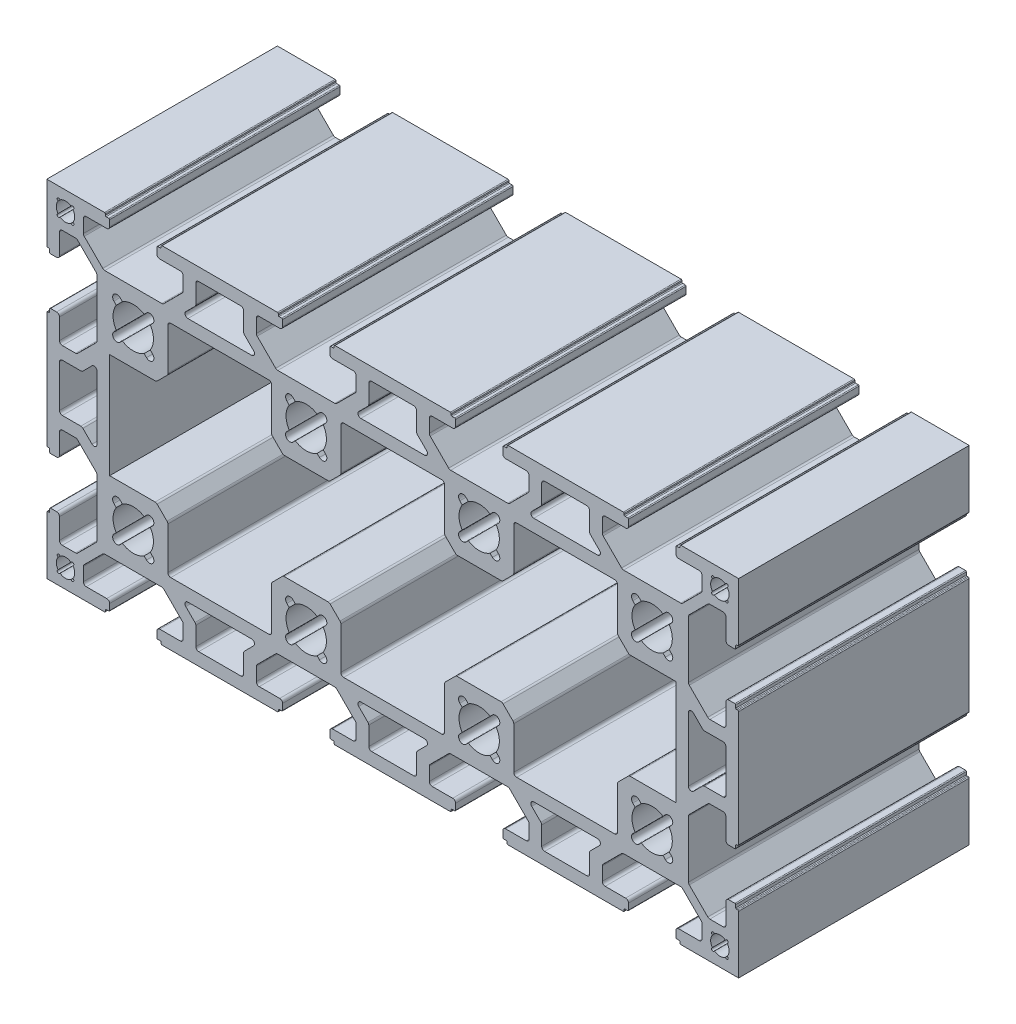
SolidWorks part; units mm, degrees
material "6061 Alaşım"
ref_plane "Ön Düzlem" through (0, 0, 0) normal (0, 0, 1) x (1, 0, 0)
ref_plane "Üst Düzlem" through (0, 0, 0) normal (0, 1, 0) x (1, 0, 0)
ref_plane "Sağ Düzlem" through (0, 0, 0) normal (1, 0, 0) x (0, 0, -1)
sketch "Referans" plane through (0, 0, 0) normal (0, 0, 1) x (1, 0, 0)
  line L0 (-15, 30) -> (-15, 0) construction
  line L1 (-60, -30) -> (60, -30) construction
  line L2 (-60, -30) -> (-60, 30) construction
  line L3 (-60, 30) -> (60, 30) construction
  line L4 (60, -30) -> (60, 30) construction
  line L5 (0, 30) -> (0, -30) construction
  line L6 (-60, 0) -> (60, 0) construction
  line L7 (-45, 30) -> (-45, 0) construction
  line L8 (-56.75, 30) -> (-56.75, 0) construction
  line L9 (-60, 26.75) -> (-56.75, 26.75) construction
  line L10 (-30, 30) -> (-30, 0) construction
  point P0 (0, 0)
  dimension "D1" = 120
  dimension "D2" = 60
  dimension "D3" = 30
  dimension "D4" = 15
  dimension "D5" = 56.75
  dimension "D6" = 26.75
  dimension "D7" = 15
sketch "Çizim3" plane through (0, 0, 0) normal (0, 0, 1) x (1, 0, 0)
  line L0 (-10.9, 28.3) -> (-10.9, 29.35)
  line L1 (-10.75, 29.5) -> (-10.3, 29.5)
  line L2 (-10.15, 29.65) -> (-10.15, 29.85)
  line L3 (-60, 30) -> (60, 30) construction
  line L4 (-10, 30) -> (10, 30)
  line L5 (-10.4, 27.8) -> (-6.85, 27.8)
  line L6 (-6.35, 27.3) -> (-6.35, 25.0071)
  line L7 (-6.4964, 24.6536) -> (-9.7036, 21.4464)
  line L8 (-10.0571, 21.3) -> (-19.9429, 21.3)
  line L9 (-15, 30) -> (-15, 0) construction
  line L10 (5.5316, 21.3) -> (-5.5316, 21.3)
  line L11 (-5.8852, 22.1536) -> (-4.2964, 23.7423)
  line L12 (-4.15, 24.0958) -> (-4.15, 27.3)
  line L13 (-3.65, 27.8) -> (3.65, 27.8)
  line L14 (0, 30) -> (0, -30) construction
  line L15 (-60, 0) -> (60, 0) construction
  line L16 (8.5, 19.1) -> (-8.5, 19.1)
  line L17 (-9, 18.6) -> (-9, 9.1) construction
  line L18 (-9, 9.1) -> (-21, 9.1) construction
  line L19 (0, 30) -> (0, 27.8) construction
  line L20 (0, 21.3) -> (0, 19.1) construction
  line L21 (-15, 21.3) -> (-15, 9.1) construction
  line L22 (-23.5036, 24.6536) -> (-20.2964, 21.4464)
  line L23 (-23.65, 27.3) -> (-23.65, 25.0071)
  line L24 (-19.6, 27.8) -> (-23.15, 27.8)
  line L25 (-19.1, 28.3) -> (-19.1, 29.35)
  line L26 (-19.25, 29.5) -> (-19.7, 29.5)
  line L27 (-19.85, 29.65) -> (-19.85, 29.85)
  line L28 (-20, 30) -> (-40, 30)
  line L29 (-30, 30) -> (-30, 27.8) construction
  line L30 (-26.35, 27.8) -> (-33.65, 27.8)
  line L31 (-25.85, 24.0958) -> (-25.85, 27.3)
  line L32 (-24.1148, 22.1536) -> (-25.7036, 23.7423)
  line L33 (-35.5316, 21.3) -> (-24.4684, 21.3)
  line L34 (-30, 21.3) -> (-30, 19.1) construction
  line L35 (-38.5, 19.1) -> (-21.5, 19.1)
  line L36 (-21, 18.6) -> (-21, 9.1) construction
  line L39 (-39, 18.6) -> (-39, 11.3071)
  line L40 (-35.8852, 22.1536) -> (-34.2964, 23.7423)
  line L41 (-34.15, 24.0958) -> (-34.15, 27.3)
  line L42 (-40.15, 29.65) -> (-40.15, 29.85)
  line L43 (-40.75, 29.5) -> (-40.3, 29.5)
  line L44 (-40.9, 28.3) -> (-40.9, 29.35)
  line L45 (-40.4, 27.8) -> (-36.85, 27.8)
  line L46 (-36.35, 27.3) -> (-36.35, 25.0071)
  line L47 (-36.4964, 24.6536) -> (-39.7036, 21.4464)
  line L48 (-40.0571, 21.3) -> (-49.9429, 21.3)
  line L49 (-45, 21.3) -> (-45, 9.1) construction
  line L51 (-49.85, 29.65) -> (-49.85, 29.85)
  line L52 (-49.25, 29.5) -> (-49.7, 29.5)
  line L53 (-49.1, 28.3) -> (-49.1, 29.35)
  line L54 (-49.6, 27.8) -> (-53.15, 27.8)
  line L55 (-53.65, 27.3) -> (-53.65, 25.0071)
  line L56 (-53.5036, 24.6536) -> (-50.2964, 21.4464)
  line L57 (-60, 30) -> (-56.75, 26.75) construction
  line L58 (-59.65, 19.85) -> (-59.85, 19.85)
  line L59 (-59.5, 19.25) -> (-59.5, 19.7)
  line L60 (-58.3, 19.1) -> (-59.35, 19.1)
  line L61 (-57.8, 19.6) -> (-57.8, 23.15)
  line L62 (-57.3, 23.65) -> (-55.0071, 23.65)
  line L63 (-54.6536, 23.5036) -> (-51.4464, 20.2964)
  line L64 (-51.3, 10.0571) -> (-51.3, 19.9429)
  line L65 (-54.6536, 6.4964) -> (-51.4464, 9.7036)
  line L66 (-57.3, 6.35) -> (-55.0071, 6.35)
  line L67 (-57.8, 10.4) -> (-57.8, 6.85)
  line L68 (-58.3, 10.9) -> (-59.35, 10.9)
  line L69 (-59.5, 10.75) -> (-59.5, 10.3)
  line L70 (-59.65, 10.15) -> (-59.85, 10.15)
  line L71 (-60, 20) -> (-60, 30)
  line L72 (-60, 30) -> (-50, 30)
  line L73 (-60, 10) -> (-60, -10)
  line L74 (-54.0958, 4.15) -> (-57.3, 4.15)
  line L75 (-52.1536, 5.8852) -> (-53.7423, 4.2964)
  line L76 (-57.8, 3.65) -> (-57.8, -3.65)
  line L77 (-51.3, 5.5316) -> (-51.3, -5.5316)
  line L78 (-49.1, -9.1) -> (-49.1, 9.1)
  line L79 (-49.1, 9.1) -> (-41.2071, 9.1)
  line L80 (-45, 15.2) -> (-42.5251, 17.6749) construction
  line L81 (-42.5251, 17.6749) -> (-42.1716, 18.0284) construction
  line L82 (-43.1129, 18.1477) -> (-42.7019, 18.5588)
  line L83 (-41.6412, 17.4981) -> (-42.0523, 17.0871)
  line L84 (-42.7019, 11.8412) -> (-43.1129, 12.2523)
  line L85 (-42.0523, 13.3129) -> (-41.6412, 12.9019)
  line L86 (-48.3588, 12.9019) -> (-47.9477, 13.3129)
  line L87 (-46.8871, 12.2523) -> (-47.2981, 11.8412)
  line L88 (-47.2981, 18.5588) -> (-46.8871, 18.1477)
  line L89 (-47.9477, 17.0871) -> (-48.3588, 17.4981)
  line L90 (-12.0523, 17.0871) -> (-11.6412, 17.4981)
  line L91 (-12.7019, 18.5588) -> (-13.1129, 18.1477)
  line L92 (-16.8871, 18.1477) -> (-17.2981, 18.5588)
  line L93 (-18.3588, 17.4981) -> (-17.9477, 17.0871)
  line L94 (-17.9477, 13.3129) -> (-18.3588, 12.9019)
  line L95 (-17.2981, 11.8412) -> (-16.8871, 12.2523)
  line L96 (-13.1129, 12.2523) -> (-12.7019, 11.8412)
  line L97 (-11.6412, 12.9019) -> (-12.0523, 13.3129)
  line L98 (-60, 0) -> (-57.8, 0) construction
  line L99 (-51.3, 0) -> (-49.1, 0) construction
  line L100 (-39.1464, 10.9536) -> (-40.8536, 9.2464)
  line L101 (-20.8536, 10.9536) -> (-19.1464, 9.2464)
  line L102 (-21, 18.6) -> (-21, 11.3071)
  line L103 (-18.7929, 9.1) -> (-11.2071, 9.1)
  line L104 (-10.8536, 9.2464) -> (-9.1464, 10.9536)
  line L105 (-9, 11.3071) -> (-9, 18.6)
  line L106 (-41, 9.1) -> (-39, 9.1) construction
  line L107 (-39, 9.1) -> (-39, 11.1) construction
  line L108 (-58.0443, 27.6907) -> (-58.1289, 27.7753)
  line L109 (-57.7753, 28.1289) -> (-57.6907, 28.0443)
  line L110 (-53.5, 30) -> (-56.75, 26.75) construction
  line L111 (-55.8093, 28.0443) -> (-55.7247, 28.1289)
  line L112 (-55.3711, 27.7753) -> (-55.4557, 27.6907)
  line L113 (-53.5, 23.5) -> (-56.75, 26.75) construction
  line L114 (-55.4557, 25.8093) -> (-55.3711, 25.7247)
  line L115 (-55.7247, 25.3711) -> (-55.8093, 25.4557)
  line L116 (-60, 23.5) -> (-56.75, 26.75) construction
  line L117 (-57.6907, 25.4557) -> (-57.7753, 25.3711)
  line L118 (-58.1289, 25.7247) -> (-58.0443, 25.8093)
  line L119 (55.4557, 25.8093) -> (55.3711, 25.7247)
  line L120 (55.7247, 25.3711) -> (55.8093, 25.4557)
  line L121 (57.6907, 25.4557) -> (57.7753, 25.3711)
  line L122 (58.1289, 25.7247) -> (58.0443, 25.8093)
  line L123 (58.0443, 27.6907) -> (58.1289, 27.7753)
  line L124 (57.7753, 28.1289) -> (57.6907, 28.0443)
  line L125 (55.8093, 28.0443) -> (55.7247, 28.1289)
  line L126 (55.3711, 27.7753) -> (55.4557, 27.6907)
  line L127 (35.8852, 22.1536) -> (34.2964, 23.7423)
  line L128 (34.15, 24.0958) -> (34.15, 27.3)
  line L129 (26.35, 27.8) -> (33.65, 27.8)
  line L130 (25.85, 24.0958) -> (25.85, 27.3)
  line L131 (24.1148, 22.1536) -> (25.7036, 23.7423)
  line L132 (35.5316, 21.3) -> (24.4684, 21.3)
  line L133 (11.6412, 12.9019) -> (12.0523, 13.3129)
  line L134 (13.1129, 12.2523) -> (12.7019, 11.8412)
  line L135 (17.2981, 11.8412) -> (16.8871, 12.2523)
  line L136 (17.9477, 13.3129) -> (18.3588, 12.9019)
  line L137 (18.3588, 17.4981) -> (17.9477, 17.0871)
  line L138 (16.8871, 18.1477) -> (17.2981, 18.5588)
  line L139 (12.7019, 18.5588) -> (13.1129, 18.1477)
  line L140 (12.0523, 17.0871) -> (11.6412, 17.4981)
  line L141 (47.9477, 17.0871) -> (48.3588, 17.4981)
  line L142 (47.2981, 18.5588) -> (46.8871, 18.1477)
  line L143 (43.1129, 18.1477) -> (42.7019, 18.5588)
  line L144 (41.6412, 17.4981) -> (42.0523, 17.0871)
  line L145 (42.0523, 13.3129) -> (41.6412, 12.9019)
  line L146 (42.7019, 11.8412) -> (43.1129, 12.2523)
  line L147 (46.8871, 12.2523) -> (47.2981, 11.8412)
  line L148 (48.3588, 12.9019) -> (47.9477, 13.3129)
  line L149 (10.4, 27.8) -> (6.85, 27.8)
  line L150 (6.35, 27.3) -> (6.35, 25.0071)
  line L151 (6.4964, 24.6536) -> (9.7036, 21.4464)
  line L152 (10.0571, 21.3) -> (19.9429, 21.3)
  line L153 (23.5036, 24.6536) -> (20.2964, 21.4464)
  line L154 (23.65, 27.3) -> (23.65, 25.0071)
  line L155 (19.6, 27.8) -> (23.15, 27.8)
  line L156 (19.1, 28.3) -> (19.1, 29.35)
  line L157 (19.25, 29.5) -> (19.7, 29.5)
  line L158 (19.85, 29.65) -> (19.85, 29.85)
  line L159 (20, 30) -> (40, 30)
  line L160 (40.15, 29.65) -> (40.15, 29.85)
  line L161 (40.75, 29.5) -> (40.3, 29.5)
  line L162 (40.9, 28.3) -> (40.9, 29.35)
  line L163 (40.4, 27.8) -> (36.85, 27.8)
  line L164 (36.35, 27.3) -> (36.35, 25.0071)
  line L165 (36.4964, 24.6536) -> (39.7036, 21.4464)
  line L166 (40.0571, 21.3) -> (49.9429, 21.3)
  line L167 (53.5036, 24.6536) -> (50.2964, 21.4464)
  line L168 (53.65, 27.3) -> (53.65, 25.0071)
  line L169 (49.6, 27.8) -> (53.15, 27.8)
  line L170 (49.1, 28.3) -> (49.1, 29.35)
  line L171 (49.25, 29.5) -> (49.7, 29.5)
  line L172 (49.85, 29.65) -> (49.85, 29.85)
  line L173 (60, 30) -> (50, 30)
  line L174 (60, 20) -> (60, 30)
  line L175 (59.65, 19.85) -> (59.85, 19.85)
  line L176 (59.5, 19.25) -> (59.5, 19.7)
  line L177 (58.3, 19.1) -> (59.35, 19.1)
  line L178 (57.8, 19.6) -> (57.8, 23.15)
  line L179 (57.3, 23.65) -> (55.0071, 23.65)
  line L180 (54.6536, 23.5036) -> (51.4464, 20.2964)
  line L181 (51.3, 10.0571) -> (51.3, 19.9429)
  line L182 (54.6536, 6.4964) -> (51.4464, 9.7036)
  line L183 (57.3, 6.35) -> (55.0071, 6.35)
  line L184 (57.8, 10.4) -> (57.8, 6.85)
  line L185 (58.3, 10.9) -> (59.35, 10.9)
  line L186 (59.5, 10.75) -> (59.5, 10.3)
  line L187 (59.65, 10.15) -> (59.85, 10.15)
  line L188 (60, 10) -> (60, -10)
  line L189 (60, 0) -> (57.8, 0) construction
  line L190 (57.8, 3.65) -> (57.8, -3.65)
  line L191 (54.0958, 4.15) -> (57.3, 4.15)
  line L192 (52.1536, 5.8852) -> (53.7423, 4.2964)
  line L193 (51.3, 5.5316) -> (51.3, -5.5316)
  line L194 (51.3, 0) -> (49.1, 0) construction
  line L195 (49.1, -9.1) -> (49.1, 9.1)
  line L196 (49.1, 9.1) -> (41.2071, 9.1)
  line L197 (39.1464, 10.9536) -> (40.8536, 9.2464)
  line L198 (39, 18.6) -> (39, 11.3071)
  line L199 (38.5, 19.1) -> (21.5, 19.1)
  line L200 (21, 18.6) -> (21, 11.3071)
  line L201 (20.8536, 10.9536) -> (19.1464, 9.2464)
  line L202 (18.7929, 9.1) -> (11.2071, 9.1)
  line L203 (10.8536, 9.2464) -> (9.1464, 10.9536)
  line L204 (9, 11.3071) -> (9, 18.6)
  line L205 (5.8852, 22.1536) -> (4.2964, 23.7423)
  line L206 (4.15, 24.0958) -> (4.15, 27.3)
  line L207 (10.15, 29.65) -> (10.15, 29.85)
  line L208 (10.75, 29.5) -> (10.3, 29.5)
  line L209 (10.9, 28.3) -> (10.9, 29.35)
  line L210 (55.3711, -27.7753) -> (55.4557, -27.6907)
  line L211 (55.8093, -28.0443) -> (55.7247, -28.1289)
  line L212 (57.7753, -28.1289) -> (57.6907, -28.0443)
  line L213 (58.0443, -27.6907) -> (58.1289, -27.7753)
  line L214 (58.1289, -25.7247) -> (58.0443, -25.8093)
  line L215 (57.6907, -25.4557) -> (57.7753, -25.3711)
  line L216 (55.7247, -25.3711) -> (55.8093, -25.4557)
  line L217 (55.4557, -25.8093) -> (55.3711, -25.7247)
  line L218 (48.3588, -12.9019) -> (47.9477, -13.3129)
  line L219 (46.8871, -12.2523) -> (47.2981, -11.8412)
  line L220 (42.7019, -11.8412) -> (43.1129, -12.2523)
  line L221 (42.0523, -13.3129) -> (41.6412, -12.9019)
  line L222 (41.6412, -17.4981) -> (42.0523, -17.0871)
  line L223 (43.1129, -18.1477) -> (42.7019, -18.5588)
  line L224 (47.2981, -18.5588) -> (46.8871, -18.1477)
  line L225 (47.9477, -17.0871) -> (48.3588, -17.4981)
  line L226 (35.5316, -21.3) -> (24.4684, -21.3)
  line L227 (24.1148, -22.1536) -> (25.7036, -23.7423)
  line L228 (25.85, -24.0958) -> (25.85, -27.3)
  line L229 (26.35, -27.8) -> (33.65, -27.8)
  line L230 (34.15, -24.0958) -> (34.15, -27.3)
  line L231 (35.8852, -22.1536) -> (34.2964, -23.7423)
  line L232 (12.0523, -17.0871) -> (11.6412, -17.4981)
  line L233 (12.7019, -18.5588) -> (13.1129, -18.1477)
  line L234 (16.8871, -18.1477) -> (17.2981, -18.5588)
  line L235 (18.3588, -17.4981) -> (17.9477, -17.0871)
  line L236 (17.9477, -13.3129) -> (18.3588, -12.9019)
  line L237 (17.2981, -11.8412) -> (16.8871, -12.2523)
  line L238 (13.1129, -12.2523) -> (12.7019, -11.8412)
  line L239 (11.6412, -12.9019) -> (12.0523, -13.3129)
  line L240 (5.8852, -22.1536) -> (4.2964, -23.7423)
  line L241 (4.15, -24.0958) -> (4.15, -27.3)
  line L242 (-3.65, -27.8) -> (3.65, -27.8)
  line L243 (-4.15, -24.0958) -> (-4.15, -27.3)
  line L244 (-5.8852, -22.1536) -> (-4.2964, -23.7423)
  line L245 (5.5316, -21.3) -> (-5.5316, -21.3)
  line L246 (-11.6412, -12.9019) -> (-12.0523, -13.3129)
  line L247 (-13.1129, -12.2523) -> (-12.7019, -11.8412)
  line L248 (-17.2981, -11.8412) -> (-16.8871, -12.2523)
  line L249 (-17.9477, -13.3129) -> (-18.3588, -12.9019)
  line L250 (-18.3588, -17.4981) -> (-17.9477, -17.0871)
  line L251 (-16.8871, -18.1477) -> (-17.2981, -18.5588)
  line L252 (-12.7019, -18.5588) -> (-13.1129, -18.1477)
  line L253 (-12.0523, -17.0871) -> (-11.6412, -17.4981)
  line L254 (-35.8852, -22.1536) -> (-34.2964, -23.7423)
  line L255 (-34.15, -24.0958) -> (-34.15, -27.3)
  line L256 (-26.35, -27.8) -> (-33.65, -27.8)
  line L257 (-25.85, -24.0958) -> (-25.85, -27.3)
  line L258 (-24.1148, -22.1536) -> (-25.7036, -23.7423)
  line L259 (-35.5316, -21.3) -> (-24.4684, -21.3)
  line L260 (-47.9477, -17.0871) -> (-48.3588, -17.4981)
  line L261 (-47.2981, -18.5588) -> (-46.8871, -18.1477)
  line L262 (-43.1129, -18.1477) -> (-42.7019, -18.5588)
  line L263 (-41.6412, -17.4981) -> (-42.0523, -17.0871)
  line L264 (-42.0523, -13.3129) -> (-41.6412, -12.9019)
  line L265 (-42.7019, -11.8412) -> (-43.1129, -12.2523)
  line L266 (-46.8871, -12.2523) -> (-47.2981, -11.8412)
  line L267 (-48.3588, -12.9019) -> (-47.9477, -13.3129)
  line L268 (-55.4557, -25.8093) -> (-55.3711, -25.7247)
  line L269 (-55.7247, -25.3711) -> (-55.8093, -25.4557)
  line L270 (-57.6907, -25.4557) -> (-57.7753, -25.3711)
  line L271 (-58.1289, -25.7247) -> (-58.0443, -25.8093)
  line L272 (-58.0443, -27.6907) -> (-58.1289, -27.7753)
  line L273 (-57.7753, -28.1289) -> (-57.6907, -28.0443)
  line L274 (-55.8093, -28.0443) -> (-55.7247, -28.1289)
  line L275 (-55.3711, -27.7753) -> (-55.4557, -27.6907)
  line L276 (10.9, -28.3) -> (10.9, -29.35)
  line L277 (10.75, -29.5) -> (10.3, -29.5)
  line L278 (10.15, -29.65) -> (10.15, -29.85)
  line L279 (-10, -30) -> (10, -30)
  line L280 (-10.15, -29.65) -> (-10.15, -29.85)
  line L281 (-10.75, -29.5) -> (-10.3, -29.5)
  line L282 (-10.9, -28.3) -> (-10.9, -29.35)
  line L283 (-10.4, -27.8) -> (-6.85, -27.8)
  line L284 (-6.35, -27.3) -> (-6.35, -25.0071)
  line L285 (-6.4964, -24.6536) -> (-9.7036, -21.4464)
  line L286 (-10.0571, -21.3) -> (-19.9429, -21.3)
  line L287 (-23.5036, -24.6536) -> (-20.2964, -21.4464)
  line L288 (-23.65, -27.3) -> (-23.65, -25.0071)
  line L289 (-19.6, -27.8) -> (-23.15, -27.8)
  line L290 (-19.1, -28.3) -> (-19.1, -29.35)
  line L291 (-19.25, -29.5) -> (-19.7, -29.5)
  line L292 (-19.85, -29.65) -> (-19.85, -29.85)
  line L293 (-20, -30) -> (-40, -30)
  line L294 (-40.15, -29.65) -> (-40.15, -29.85)
  line L295 (-40.75, -29.5) -> (-40.3, -29.5)
  line L296 (-40.9, -28.3) -> (-40.9, -29.35)
  line L297 (-40.4, -27.8) -> (-36.85, -27.8)
  line L298 (-36.35, -27.3) -> (-36.35, -25.0071)
  line L299 (-36.4964, -24.6536) -> (-39.7036, -21.4464)
  line L300 (-40.0571, -21.3) -> (-49.9429, -21.3)
  line L301 (-53.5036, -24.6536) -> (-50.2964, -21.4464)
  line L302 (-53.65, -27.3) -> (-53.65, -25.0071)
  line L303 (-49.6, -27.8) -> (-53.15, -27.8)
  line L304 (-49.1, -28.3) -> (-49.1, -29.35)
  line L305 (-49.25, -29.5) -> (-49.7, -29.5)
  line L306 (-49.85, -29.65) -> (-49.85, -29.85)
  line L307 (-60, -30) -> (-50, -30)
  line L308 (-60, -20) -> (-60, -30)
  line L309 (-59.65, -19.85) -> (-59.85, -19.85)
  line L310 (-59.5, -19.25) -> (-59.5, -19.7)
  line L311 (-58.3, -19.1) -> (-59.35, -19.1)
  line L312 (-57.8, -19.6) -> (-57.8, -23.15)
  line L313 (-57.3, -23.65) -> (-55.0071, -23.65)
  line L314 (-54.6536, -23.5036) -> (-51.4464, -20.2964)
  line L315 (-51.3, -10.0571) -> (-51.3, -19.9429)
  line L316 (-54.6536, -6.4964) -> (-51.4464, -9.7036)
  line L317 (-57.3, -6.35) -> (-55.0071, -6.35)
  line L318 (-57.8, -10.4) -> (-57.8, -6.85)
  line L319 (-58.3, -10.9) -> (-59.35, -10.9)
  line L320 (-59.5, -10.75) -> (-59.5, -10.3)
  line L321 (-59.65, -10.15) -> (-59.85, -10.15)
  line L322 (-54.0958, -4.15) -> (-57.3, -4.15)
  line L323 (-52.1536, -5.8852) -> (-53.7423, -4.2964)
  line L324 (-49.1, -9.1) -> (-41.2071, -9.1)
  line L325 (-39.1464, -10.9536) -> (-40.8536, -9.2464)
  line L326 (-39, -18.6) -> (-39, -11.3071)
  line L327 (-38.5, -19.1) -> (-21.5, -19.1)
  line L328 (-21, -18.6) -> (-21, -11.3071)
  line L329 (-20.8536, -10.9536) -> (-19.1464, -9.2464)
  line L330 (-18.7929, -9.1) -> (-11.2071, -9.1)
  line L331 (-10.8536, -9.2464) -> (-9.1464, -10.9536)
  line L332 (-9, -11.3071) -> (-9, -18.6)
  line L333 (8.5, -19.1) -> (-8.5, -19.1)
  line L334 (9, -11.3071) -> (9, -18.6)
  line L335 (10.8536, -9.2464) -> (9.1464, -10.9536)
  line L336 (18.7929, -9.1) -> (11.2071, -9.1)
  line L337 (20.8536, -10.9536) -> (19.1464, -9.2464)
  line L338 (21, -18.6) -> (21, -11.3071)
  line L339 (38.5, -19.1) -> (21.5, -19.1)
  line L340 (39, -18.6) -> (39, -11.3071)
  line L341 (39.1464, -10.9536) -> (40.8536, -9.2464)
  line L342 (49.1, -9.1) -> (41.2071, -9.1)
  line L343 (52.1536, -5.8852) -> (53.7423, -4.2964)
  line L344 (54.0958, -4.15) -> (57.3, -4.15)
  line L345 (59.65, -10.15) -> (59.85, -10.15)
  line L346 (59.5, -10.75) -> (59.5, -10.3)
  line L347 (58.3, -10.9) -> (59.35, -10.9)
  line L348 (57.8, -10.4) -> (57.8, -6.85)
  line L349 (57.3, -6.35) -> (55.0071, -6.35)
  line L350 (54.6536, -6.4964) -> (51.4464, -9.7036)
  line L351 (51.3, -10.0571) -> (51.3, -19.9429)
  line L352 (54.6536, -23.5036) -> (51.4464, -20.2964)
  line L353 (57.3, -23.65) -> (55.0071, -23.65)
  line L354 (57.8, -19.6) -> (57.8, -23.15)
  line L355 (58.3, -19.1) -> (59.35, -19.1)
  line L356 (59.5, -19.25) -> (59.5, -19.7)
  line L357 (59.65, -19.85) -> (59.85, -19.85)
  line L358 (60, -20) -> (60, -30)
  line L359 (60, -30) -> (50, -30)
  line L360 (49.85, -29.65) -> (49.85, -29.85)
  line L361 (49.25, -29.5) -> (49.7, -29.5)
  line L362 (49.1, -28.3) -> (49.1, -29.35)
  line L363 (49.6, -27.8) -> (53.15, -27.8)
  line L364 (53.65, -27.3) -> (53.65, -25.0071)
  line L365 (53.5036, -24.6536) -> (50.2964, -21.4464)
  line L366 (40.0571, -21.3) -> (49.9429, -21.3)
  line L367 (36.4964, -24.6536) -> (39.7036, -21.4464)
  line L368 (36.35, -27.3) -> (36.35, -25.0071)
  line L369 (40.4, -27.8) -> (36.85, -27.8)
  line L370 (40.9, -28.3) -> (40.9, -29.35)
  line L371 (40.75, -29.5) -> (40.3, -29.5)
  line L372 (40.15, -29.65) -> (40.15, -29.85)
  line L373 (20, -30) -> (40, -30)
  line L374 (19.85, -29.65) -> (19.85, -29.85)
  line L375 (19.25, -29.5) -> (19.7, -29.5)
  line L376 (19.1, -28.3) -> (19.1, -29.35)
  line L377 (19.6, -27.8) -> (23.15, -27.8)
  line L378 (23.65, -27.3) -> (23.65, -25.0071)
  line L379 (23.5036, -24.6536) -> (20.2964, -21.4464)
  line L380 (10.0571, -21.3) -> (19.9429, -21.3)
  line L381 (6.4964, -24.6536) -> (9.7036, -21.4464)
  line L382 (6.35, -27.3) -> (6.35, -25.0071)
  line L383 (10.4, -27.8) -> (6.85, -27.8)
  circle A0 centre (-56.75, 26.75) radius 1.6 construction
  circle A1 centre (-15, 15) radius 3.5 construction
  arc A2 (-10.9, 28.3) -> (-10.4, 27.8) centre (-10.4, 28.3) ccw
  arc A3 (-9.7036, 21.4464) -> (-10.0571, 21.3) centre (-10.0571, 21.8) cw
  arc A4 (-6.35, 25.0071) -> (-6.4964, 24.6536) centre (-6.85, 25.0071) cw
  arc A5 (-6.85, 27.8) -> (-6.35, 27.3) centre (-6.85, 27.3) cw
  arc A6 (-4.15, 27.3) -> (-3.65, 27.8) centre (-3.65, 27.3) cw
  arc A7 (-4.2964, 23.7423) -> (-4.15, 24.0958) centre (-4.65, 24.0958) ccw
  arc A8 (-5.5316, 21.3) -> (-5.8852, 22.1536) centre (-5.5316, 21.8) cw
  arc A9 (-8.5, 19.1) -> (-9, 18.6) centre (-8.5, 18.6) ccw
  arc A10 (-10.9, 29.35) -> (-10.75, 29.5) centre (-10.75, 29.35) cw
  arc A11 (-10.3, 29.5) -> (-10.15, 29.65) centre (-10.3, 29.65) ccw
  arc A12 (-10.15, 29.85) -> (-10, 30) centre (-10, 29.85) cw
  arc A13 (-20.2964, 21.4464) -> (-19.9429, 21.3) centre (-19.9429, 21.8) ccw
  arc A14 (-23.65, 25.0071) -> (-23.5036, 24.6536) centre (-23.15, 25.0071) ccw
  arc A15 (-23.15, 27.8) -> (-23.65, 27.3) centre (-23.15, 27.3) ccw
  arc A16 (-19.1, 28.3) -> (-19.6, 27.8) centre (-19.6, 28.3) cw
  arc A17 (-19.1, 29.35) -> (-19.25, 29.5) centre (-19.25, 29.35) ccw
  arc A18 (-19.7, 29.5) -> (-19.85, 29.65) centre (-19.7, 29.65) cw
  arc A19 (-19.85, 29.85) -> (-20, 30) centre (-20, 29.85) ccw
  arc A20 (-25.85, 27.3) -> (-26.35, 27.8) centre (-26.35, 27.3) ccw
  arc A21 (-25.7036, 23.7423) -> (-25.85, 24.0958) centre (-25.35, 24.0958) cw
  arc A22 (-24.4684, 21.3) -> (-24.1148, 22.1536) centre (-24.4684, 21.8) ccw
  arc A23 (-21.5, 19.1) -> (-21, 18.6) centre (-21.5, 18.6) cw
  arc A24 (-38.5, 19.1) -> (-39, 18.6) centre (-38.5, 18.6) ccw
  arc A25 (-35.5316, 21.3) -> (-35.8852, 22.1536) centre (-35.5316, 21.8) cw
  arc A26 (-34.2964, 23.7423) -> (-34.15, 24.0958) centre (-34.65, 24.0958) ccw
  arc A27 (-34.15, 27.3) -> (-33.65, 27.8) centre (-33.65, 27.3) cw
  arc A28 (-40.15, 29.85) -> (-40, 30) centre (-40, 29.85) cw
  arc A29 (-40.3, 29.5) -> (-40.15, 29.65) centre (-40.3, 29.65) ccw
  arc A30 (-40.9, 29.35) -> (-40.75, 29.5) centre (-40.75, 29.35) cw
  arc A31 (-40.9, 28.3) -> (-40.4, 27.8) centre (-40.4, 28.3) ccw
  arc A32 (-36.85, 27.8) -> (-36.35, 27.3) centre (-36.85, 27.3) cw
  arc A33 (-36.35, 25.0071) -> (-36.4964, 24.6536) centre (-36.85, 25.0071) cw
  arc A34 (-39.7036, 21.4464) -> (-40.0571, 21.3) centre (-40.0571, 21.8) cw
  arc A35 (-49.85, 29.85) -> (-50, 30) centre (-50, 29.85) ccw
  arc A36 (-49.7, 29.5) -> (-49.85, 29.65) centre (-49.7, 29.65) cw
  arc A37 (-49.1, 29.35) -> (-49.25, 29.5) centre (-49.25, 29.35) ccw
  arc A38 (-49.1, 28.3) -> (-49.6, 27.8) centre (-49.6, 28.3) cw
  arc A39 (-53.15, 27.8) -> (-53.65, 27.3) centre (-53.15, 27.3) ccw
  arc A40 (-53.65, 25.0071) -> (-53.5036, 24.6536) centre (-53.15, 25.0071) ccw
  arc A41 (-50.2964, 21.4464) -> (-49.9429, 21.3) centre (-49.9429, 21.8) ccw
  arc A42 (-59.85, 19.85) -> (-60, 20) centre (-59.85, 20) cw
  arc A43 (-59.5, 19.7) -> (-59.65, 19.85) centre (-59.65, 19.7) ccw
  arc A44 (-59.35, 19.1) -> (-59.5, 19.25) centre (-59.35, 19.25) cw
  arc A45 (-58.3, 19.1) -> (-57.8, 19.6) centre (-58.3, 19.6) ccw
  arc A46 (-57.8, 23.15) -> (-57.3, 23.65) centre (-57.3, 23.15) cw
  arc A47 (-55.0071, 23.65) -> (-54.6536, 23.5036) centre (-55.0071, 23.15) cw
  arc A48 (-51.4464, 20.2964) -> (-51.3, 19.9429) centre (-51.8, 19.9429) cw
  arc A49 (-51.4464, 9.7036) -> (-51.3, 10.0571) centre (-51.8, 10.0571) ccw
  arc A50 (-55.0071, 6.35) -> (-54.6536, 6.4964) centre (-55.0071, 6.85) ccw
  arc A51 (-57.8, 6.85) -> (-57.3, 6.35) centre (-57.3, 6.85) ccw
  arc A52 (-58.3, 10.9) -> (-57.8, 10.4) centre (-58.3, 10.4) cw
  arc A53 (-59.35, 10.9) -> (-59.5, 10.75) centre (-59.35, 10.75) ccw
  arc A54 (-59.5, 10.3) -> (-59.65, 10.15) centre (-59.65, 10.3) cw
  arc A55 (-59.85, 10.15) -> (-60, 10) centre (-59.85, 10) ccw
  arc A56 (-57.3, 4.15) -> (-57.8, 3.65) centre (-57.3, 3.65) ccw
  arc A57 (-53.7423, 4.2964) -> (-54.0958, 4.15) centre (-54.0958, 4.65) cw
  arc A58 (-51.3, 5.5316) -> (-52.1536, 5.8852) centre (-51.8, 5.5316) ccw
  circle A59 centre (-45, 15.2) radius 3.5 construction
  arc A60 (-42.7019, 18.5588) -> (-41.6412, 17.4981) centre (-42.1716, 18.0284) cw
  arc A61 (-41.6412, 12.9019) -> (-42.7019, 11.8412) centre (-42.1716, 12.3716) cw
  circle A62 centre (-45, 15.2) radius 3.5 construction
  arc A63 (-47.2981, 11.8412) -> (-48.3588, 12.9019) centre (-47.8284, 12.3716) cw
  circle A64 centre (-45, 15.2) radius 3.5 construction
  arc A65 (-48.3588, 17.4981) -> (-47.2981, 18.5588) centre (-47.8284, 18.0284) cw
  circle A66 centre (-45, 15.2) radius 3.5 construction
  arc A67 (-46.8871, 18.1477) -> (-43.1129, 18.1477) centre (-45, 15.2) cw
  arc A68 (-42.0523, 17.0871) -> (-42.0523, 13.3129) centre (-45, 15.2) cw
  arc A69 (-43.1129, 12.2523) -> (-46.8871, 12.2523) centre (-45, 15.2) cw
  arc A70 (-47.9477, 17.0871) -> (-47.9477, 13.3129) centre (-45, 15.2) ccw
  arc A71 (-11.6412, 17.4981) -> (-12.7019, 18.5588) centre (-12.1716, 18.0284) ccw
  arc A72 (-13.1129, 18.1477) -> (-16.8871, 18.1477) centre (-15, 15.2) ccw
  arc A73 (-17.2981, 18.5588) -> (-18.3588, 17.4981) centre (-17.8284, 18.0284) ccw
  arc A74 (-17.9477, 17.0871) -> (-17.9477, 13.3129) centre (-15, 15.2) ccw
  arc A75 (-18.3588, 12.9019) -> (-17.2981, 11.8412) centre (-17.8284, 12.3716) ccw
  arc A76 (-16.8871, 12.2523) -> (-13.1129, 12.2523) centre (-15, 15.2) ccw
  arc A77 (-12.7019, 11.8412) -> (-11.6412, 12.9019) centre (-12.1716, 12.3716) ccw
  arc A78 (-12.0523, 17.0871) -> (-12.0523, 13.3129) centre (-15, 15.2) cw
  arc A79 (-9.1464, 10.9536) -> (-9, 11.3071) centre (-9.5, 11.3071) ccw
  arc A80 (-11.2071, 9.1) -> (-10.8536, 9.2464) centre (-11.2071, 9.6) ccw
  arc A81 (-19.1464, 9.2464) -> (-18.7929, 9.1) centre (-18.7929, 9.6) ccw
  arc A82 (-20.8536, 10.9536) -> (-21, 11.3071) centre (-20.5, 11.3071) cw
  arc A83 (-39.1464, 10.9536) -> (-39, 11.3071) centre (-39.5, 11.3071) ccw
  arc A84 (-40.8536, 9.2464) -> (-41.2071, 9.1) centre (-41.2071, 9.6) cw
  arc A85 (-58.1289, 27.7753) -> (-57.7753, 28.1289) centre (-57.9521, 27.9521) cw
  arc A86 (-55.7247, 28.1289) -> (-55.3711, 27.7753) centre (-55.5479, 27.9521) cw
  arc A87 (-55.3711, 25.7247) -> (-55.7247, 25.3711) centre (-55.5479, 25.5479) cw
  arc A88 (-57.7753, 25.3711) -> (-58.1289, 25.7247) centre (-57.9521, 25.5479) cw
  arc A89 (-57.6907, 28.0443) -> (-55.8093, 28.0443) centre (-56.75, 26.75) cw
  arc A90 (-58.0443, 27.6907) -> (-58.0443, 25.8093) centre (-56.75, 26.75) ccw
  arc A91 (-57.6907, 25.4557) -> (-55.8093, 25.4557) centre (-56.75, 26.75) ccw
  arc A92 (-55.4557, 25.8093) -> (-55.4557, 27.6907) centre (-56.75, 26.75) ccw
  arc A93 (55.3711, 25.7247) -> (55.7247, 25.3711) centre (55.5479, 25.5479) ccw
  arc A94 (57.6907, 25.4557) -> (55.8093, 25.4557) centre (56.75, 26.75) cw
  arc A95 (57.7753, 25.3711) -> (58.1289, 25.7247) centre (57.9521, 25.5479) ccw
  arc A96 (58.0443, 27.6907) -> (58.0443, 25.8093) centre (56.75, 26.75) cw
  arc A97 (58.1289, 27.7753) -> (57.7753, 28.1289) centre (57.9521, 27.9521) ccw
  arc A98 (57.6907, 28.0443) -> (55.8093, 28.0443) centre (56.75, 26.75) ccw
  arc A99 (55.7247, 28.1289) -> (55.3711, 27.7753) centre (55.5479, 27.9521) ccw
  arc A100 (55.4557, 25.8093) -> (55.4557, 27.6907) centre (56.75, 26.75) cw
  arc A101 (35.5316, 21.3) -> (35.8852, 22.1536) centre (35.5316, 21.8) ccw
  arc A102 (34.2964, 23.7423) -> (34.15, 24.0958) centre (34.65, 24.0958) cw
  arc A103 (34.15, 27.3) -> (33.65, 27.8) centre (33.65, 27.3) ccw
  arc A104 (25.85, 27.3) -> (26.35, 27.8) centre (26.35, 27.3) cw
  arc A105 (25.7036, 23.7423) -> (25.85, 24.0958) centre (25.35, 24.0958) ccw
  arc A106 (24.4684, 21.3) -> (24.1148, 22.1536) centre (24.4684, 21.8) cw
  arc A107 (12.0523, 17.0871) -> (12.0523, 13.3129) centre (15, 15.2) ccw
  arc A108 (12.7019, 11.8412) -> (11.6412, 12.9019) centre (12.1716, 12.3716) cw
  arc A109 (16.8871, 12.2523) -> (13.1129, 12.2523) centre (15, 15.2) cw
  arc A110 (18.3588, 12.9019) -> (17.2981, 11.8412) centre (17.8284, 12.3716) cw
  arc A111 (17.9477, 17.0871) -> (17.9477, 13.3129) centre (15, 15.2) cw
  arc A112 (17.2981, 18.5588) -> (18.3588, 17.4981) centre (17.8284, 18.0284) cw
  arc A113 (13.1129, 18.1477) -> (16.8871, 18.1477) centre (15, 15.2) cw
  arc A114 (11.6412, 17.4981) -> (12.7019, 18.5588) centre (12.1716, 18.0284) cw
  arc A115 (48.3588, 17.4981) -> (47.2981, 18.5588) centre (47.8284, 18.0284) ccw
  arc A116 (46.8871, 18.1477) -> (43.1129, 18.1477) centre (45, 15.2) ccw
  arc A117 (42.7019, 18.5588) -> (41.6412, 17.4981) centre (42.1716, 18.0284) ccw
  arc A118 (42.0523, 17.0871) -> (42.0523, 13.3129) centre (45, 15.2) ccw
  arc A119 (41.6412, 12.9019) -> (42.7019, 11.8412) centre (42.1716, 12.3716) ccw
  arc A120 (43.1129, 12.2523) -> (46.8871, 12.2523) centre (45, 15.2) ccw
  arc A121 (47.2981, 11.8412) -> (48.3588, 12.9019) centre (47.8284, 12.3716) ccw
  arc A122 (47.9477, 17.0871) -> (47.9477, 13.3129) centre (45, 15.2) cw
  arc A123 (10.9, 28.3) -> (10.4, 27.8) centre (10.4, 28.3) cw
  arc A124 (6.85, 27.8) -> (6.35, 27.3) centre (6.85, 27.3) ccw
  arc A125 (6.35, 25.0071) -> (6.4964, 24.6536) centre (6.85, 25.0071) ccw
  arc A126 (9.7036, 21.4464) -> (10.0571, 21.3) centre (10.0571, 21.8) ccw
  arc A127 (20.2964, 21.4464) -> (19.9429, 21.3) centre (19.9429, 21.8) cw
  arc A128 (23.65, 25.0071) -> (23.5036, 24.6536) centre (23.15, 25.0071) cw
  arc A129 (23.15, 27.8) -> (23.65, 27.3) centre (23.15, 27.3) cw
  arc A130 (19.1, 28.3) -> (19.6, 27.8) centre (19.6, 28.3) ccw
  arc A131 (19.1, 29.35) -> (19.25, 29.5) centre (19.25, 29.35) cw
  arc A132 (19.7, 29.5) -> (19.85, 29.65) centre (19.7, 29.65) ccw
  arc A133 (19.85, 29.85) -> (20, 30) centre (20, 29.85) cw
  arc A134 (40.15, 29.85) -> (40, 30) centre (40, 29.85) ccw
  arc A135 (40.3, 29.5) -> (40.15, 29.65) centre (40.3, 29.65) cw
  arc A136 (40.9, 29.35) -> (40.75, 29.5) centre (40.75, 29.35) ccw
  arc A137 (40.9, 28.3) -> (40.4, 27.8) centre (40.4, 28.3) cw
  arc A138 (36.85, 27.8) -> (36.35, 27.3) centre (36.85, 27.3) ccw
  arc A139 (36.35, 25.0071) -> (36.4964, 24.6536) centre (36.85, 25.0071) ccw
  arc A140 (39.7036, 21.4464) -> (40.0571, 21.3) centre (40.0571, 21.8) ccw
  arc A141 (50.2964, 21.4464) -> (49.9429, 21.3) centre (49.9429, 21.8) cw
  arc A142 (53.65, 25.0071) -> (53.5036, 24.6536) centre (53.15, 25.0071) cw
  arc A143 (53.15, 27.8) -> (53.65, 27.3) centre (53.15, 27.3) cw
  arc A144 (49.1, 28.3) -> (49.6, 27.8) centre (49.6, 28.3) ccw
  arc A145 (49.1, 29.35) -> (49.25, 29.5) centre (49.25, 29.35) cw
  arc A146 (49.7, 29.5) -> (49.85, 29.65) centre (49.7, 29.65) ccw
  arc A147 (49.85, 29.85) -> (50, 30) centre (50, 29.85) cw
  arc A148 (59.85, 19.85) -> (60, 20) centre (59.85, 20) ccw
  arc A149 (59.5, 19.7) -> (59.65, 19.85) centre (59.65, 19.7) cw
  arc A150 (59.35, 19.1) -> (59.5, 19.25) centre (59.35, 19.25) ccw
  arc A151 (58.3, 19.1) -> (57.8, 19.6) centre (58.3, 19.6) cw
  arc A152 (57.8, 23.15) -> (57.3, 23.65) centre (57.3, 23.15) ccw
  arc A153 (55.0071, 23.65) -> (54.6536, 23.5036) centre (55.0071, 23.15) ccw
  arc A154 (51.4464, 20.2964) -> (51.3, 19.9429) centre (51.8, 19.9429) ccw
  arc A155 (51.4464, 9.7036) -> (51.3, 10.0571) centre (51.8, 10.0571) cw
  arc A156 (55.0071, 6.35) -> (54.6536, 6.4964) centre (55.0071, 6.85) cw
  arc A157 (57.8, 6.85) -> (57.3, 6.35) centre (57.3, 6.85) cw
  arc A158 (58.3, 10.9) -> (57.8, 10.4) centre (58.3, 10.4) ccw
  arc A159 (59.35, 10.9) -> (59.5, 10.75) centre (59.35, 10.75) cw
  arc A160 (59.5, 10.3) -> (59.65, 10.15) centre (59.65, 10.3) ccw
  arc A161 (59.85, 10.15) -> (60, 10) centre (59.85, 10) cw
  arc A162 (57.3, 4.15) -> (57.8, 3.65) centre (57.3, 3.65) cw
  arc A163 (53.7423, 4.2964) -> (54.0958, 4.15) centre (54.0958, 4.65) ccw
  arc A164 (51.3, 5.5316) -> (52.1536, 5.8852) centre (51.8, 5.5316) cw
  arc A165 (40.8536, 9.2464) -> (41.2071, 9.1) centre (41.2071, 9.6) ccw
  arc A166 (39.1464, 10.9536) -> (39, 11.3071) centre (39.5, 11.3071) cw
  arc A167 (38.5, 19.1) -> (39, 18.6) centre (38.5, 18.6) cw
  arc A168 (21.5, 19.1) -> (21, 18.6) centre (21.5, 18.6) ccw
  arc A169 (20.8536, 10.9536) -> (21, 11.3071) centre (20.5, 11.3071) ccw
  arc A170 (19.1464, 9.2464) -> (18.7929, 9.1) centre (18.7929, 9.6) cw
  arc A171 (11.2071, 9.1) -> (10.8536, 9.2464) centre (11.2071, 9.6) cw
  arc A172 (9.1464, 10.9536) -> (9, 11.3071) centre (9.5, 11.3071) cw
  arc A173 (8.5, 19.1) -> (9, 18.6) centre (8.5, 18.6) cw
  arc A174 (5.5316, 21.3) -> (5.8852, 22.1536) centre (5.5316, 21.8) ccw
  arc A175 (4.2964, 23.7423) -> (4.15, 24.0958) centre (4.65, 24.0958) cw
  arc A176 (4.15, 27.3) -> (3.65, 27.8) centre (3.65, 27.3) ccw
  arc A177 (10.15, 29.85) -> (10, 30) centre (10, 29.85) ccw
  arc A178 (10.3, 29.5) -> (10.15, 29.65) centre (10.3, 29.65) cw
  arc A179 (10.9, 29.35) -> (10.75, 29.5) centre (10.75, 29.35) ccw
  arc A180 (55.4557, -25.8093) -> (55.4557, -27.6907) centre (56.75, -26.75) ccw
  arc A181 (55.7247, -28.1289) -> (55.3711, -27.7753) centre (55.5479, -27.9521) cw
  arc A182 (57.6907, -28.0443) -> (55.8093, -28.0443) centre (56.75, -26.75) cw
  arc A183 (58.1289, -27.7753) -> (57.7753, -28.1289) centre (57.9521, -27.9521) cw
  arc A184 (58.0443, -27.6907) -> (58.0443, -25.8093) centre (56.75, -26.75) ccw
  arc A185 (57.7753, -25.3711) -> (58.1289, -25.7247) centre (57.9521, -25.5479) cw
  arc A186 (57.6907, -25.4557) -> (55.8093, -25.4557) centre (56.75, -26.75) ccw
  arc A187 (55.3711, -25.7247) -> (55.7247, -25.3711) centre (55.5479, -25.5479) cw
  arc A188 (47.9477, -17.0871) -> (47.9477, -13.3129) centre (45, -15.2) ccw
  arc A189 (47.2981, -11.8412) -> (48.3588, -12.9019) centre (47.8284, -12.3716) cw
  arc A190 (43.1129, -12.2523) -> (46.8871, -12.2523) centre (45, -15.2) cw
  arc A191 (41.6412, -12.9019) -> (42.7019, -11.8412) centre (42.1716, -12.3716) cw
  arc A192 (42.0523, -17.0871) -> (42.0523, -13.3129) centre (45, -15.2) cw
  arc A193 (42.7019, -18.5588) -> (41.6412, -17.4981) centre (42.1716, -18.0284) cw
  arc A194 (46.8871, -18.1477) -> (43.1129, -18.1477) centre (45, -15.2) cw
  arc A195 (48.3588, -17.4981) -> (47.2981, -18.5588) centre (47.8284, -18.0284) cw
  arc A196 (24.4684, -21.3) -> (24.1148, -22.1536) centre (24.4684, -21.8) ccw
  arc A197 (25.7036, -23.7423) -> (25.85, -24.0958) centre (25.35, -24.0958) cw
  arc A198 (25.85, -27.3) -> (26.35, -27.8) centre (26.35, -27.3) ccw
  arc A199 (34.15, -27.3) -> (33.65, -27.8) centre (33.65, -27.3) cw
  arc A200 (34.2964, -23.7423) -> (34.15, -24.0958) centre (34.65, -24.0958) ccw
  arc A201 (35.5316, -21.3) -> (35.8852, -22.1536) centre (35.5316, -21.8) cw
  arc A202 (11.6412, -17.4981) -> (12.7019, -18.5588) centre (12.1716, -18.0284) ccw
  arc A203 (13.1129, -18.1477) -> (16.8871, -18.1477) centre (15, -15.2) ccw
  arc A204 (17.2981, -18.5588) -> (18.3588, -17.4981) centre (17.8284, -18.0284) ccw
  arc A205 (17.9477, -17.0871) -> (17.9477, -13.3129) centre (15, -15.2) ccw
  arc A206 (18.3588, -12.9019) -> (17.2981, -11.8412) centre (17.8284, -12.3716) ccw
  arc A207 (16.8871, -12.2523) -> (13.1129, -12.2523) centre (15, -15.2) ccw
  arc A208 (12.7019, -11.8412) -> (11.6412, -12.9019) centre (12.1716, -12.3716) ccw
  arc A209 (12.0523, -17.0871) -> (12.0523, -13.3129) centre (15, -15.2) cw
  arc A210 (5.5316, -21.3) -> (5.8852, -22.1536) centre (5.5316, -21.8) cw
  arc A211 (4.2964, -23.7423) -> (4.15, -24.0958) centre (4.65, -24.0958) ccw
  arc A212 (4.15, -27.3) -> (3.65, -27.8) centre (3.65, -27.3) cw
  arc A213 (-4.15, -27.3) -> (-3.65, -27.8) centre (-3.65, -27.3) ccw
  arc A214 (-4.2964, -23.7423) -> (-4.15, -24.0958) centre (-4.65, -24.0958) cw
  arc A215 (-5.5316, -21.3) -> (-5.8852, -22.1536) centre (-5.5316, -21.8) ccw
  arc A216 (-12.0523, -17.0871) -> (-12.0523, -13.3129) centre (-15, -15.2) ccw
  arc A217 (-12.7019, -11.8412) -> (-11.6412, -12.9019) centre (-12.1716, -12.3716) cw
  arc A218 (-16.8871, -12.2523) -> (-13.1129, -12.2523) centre (-15, -15.2) cw
  arc A219 (-18.3588, -12.9019) -> (-17.2981, -11.8412) centre (-17.8284, -12.3716) cw
  arc A220 (-17.9477, -17.0871) -> (-17.9477, -13.3129) centre (-15, -15.2) cw
  arc A221 (-17.2981, -18.5588) -> (-18.3588, -17.4981) centre (-17.8284, -18.0284) cw
  arc A222 (-13.1129, -18.1477) -> (-16.8871, -18.1477) centre (-15, -15.2) cw
  arc A223 (-11.6412, -17.4981) -> (-12.7019, -18.5588) centre (-12.1716, -18.0284) cw
  arc A224 (-35.5316, -21.3) -> (-35.8852, -22.1536) centre (-35.5316, -21.8) ccw
  arc A225 (-34.2964, -23.7423) -> (-34.15, -24.0958) centre (-34.65, -24.0958) cw
  arc A226 (-34.15, -27.3) -> (-33.65, -27.8) centre (-33.65, -27.3) ccw
  arc A227 (-25.85, -27.3) -> (-26.35, -27.8) centre (-26.35, -27.3) cw
  arc A228 (-25.7036, -23.7423) -> (-25.85, -24.0958) centre (-25.35, -24.0958) ccw
  arc A229 (-24.4684, -21.3) -> (-24.1148, -22.1536) centre (-24.4684, -21.8) cw
  arc A230 (-48.3588, -17.4981) -> (-47.2981, -18.5588) centre (-47.8284, -18.0284) ccw
  arc A231 (-46.8871, -18.1477) -> (-43.1129, -18.1477) centre (-45, -15.2) ccw
  arc A232 (-42.7019, -18.5588) -> (-41.6412, -17.4981) centre (-42.1716, -18.0284) ccw
  arc A233 (-42.0523, -17.0871) -> (-42.0523, -13.3129) centre (-45, -15.2) ccw
  arc A234 (-41.6412, -12.9019) -> (-42.7019, -11.8412) centre (-42.1716, -12.3716) ccw
  arc A235 (-43.1129, -12.2523) -> (-46.8871, -12.2523) centre (-45, -15.2) ccw
  arc A236 (-47.2981, -11.8412) -> (-48.3588, -12.9019) centre (-47.8284, -12.3716) ccw
  arc A237 (-47.9477, -17.0871) -> (-47.9477, -13.3129) centre (-45, -15.2) cw
  arc A238 (-55.3711, -25.7247) -> (-55.7247, -25.3711) centre (-55.5479, -25.5479) ccw
  arc A239 (-57.6907, -25.4557) -> (-55.8093, -25.4557) centre (-56.75, -26.75) cw
  arc A240 (-57.7753, -25.3711) -> (-58.1289, -25.7247) centre (-57.9521, -25.5479) ccw
  arc A241 (-58.0443, -27.6907) -> (-58.0443, -25.8093) centre (-56.75, -26.75) cw
  arc A242 (-58.1289, -27.7753) -> (-57.7753, -28.1289) centre (-57.9521, -27.9521) ccw
  arc A243 (-57.6907, -28.0443) -> (-55.8093, -28.0443) centre (-56.75, -26.75) ccw
  arc A244 (-55.7247, -28.1289) -> (-55.3711, -27.7753) centre (-55.5479, -27.9521) ccw
  arc A245 (-55.4557, -25.8093) -> (-55.4557, -27.6907) centre (-56.75, -26.75) cw
  arc A246 (10.9, -29.35) -> (10.75, -29.5) centre (10.75, -29.35) cw
  arc A247 (10.3, -29.5) -> (10.15, -29.65) centre (10.3, -29.65) ccw
  arc A248 (10.15, -29.85) -> (10, -30) centre (10, -29.85) cw
  arc A249 (-10.15, -29.85) -> (-10, -30) centre (-10, -29.85) ccw
  arc A250 (-10.3, -29.5) -> (-10.15, -29.65) centre (-10.3, -29.65) cw
  arc A251 (-10.9, -29.35) -> (-10.75, -29.5) centre (-10.75, -29.35) ccw
  arc A252 (-10.9, -28.3) -> (-10.4, -27.8) centre (-10.4, -28.3) cw
  arc A253 (-6.85, -27.8) -> (-6.35, -27.3) centre (-6.85, -27.3) ccw
  arc A254 (-6.35, -25.0071) -> (-6.4964, -24.6536) centre (-6.85, -25.0071) ccw
  arc A255 (-9.7036, -21.4464) -> (-10.0571, -21.3) centre (-10.0571, -21.8) ccw
  arc A256 (-20.2964, -21.4464) -> (-19.9429, -21.3) centre (-19.9429, -21.8) cw
  arc A257 (-23.65, -25.0071) -> (-23.5036, -24.6536) centre (-23.15, -25.0071) cw
  arc A258 (-23.15, -27.8) -> (-23.65, -27.3) centre (-23.15, -27.3) cw
  arc A259 (-19.1, -28.3) -> (-19.6, -27.8) centre (-19.6, -28.3) ccw
  arc A260 (-19.1, -29.35) -> (-19.25, -29.5) centre (-19.25, -29.35) cw
  arc A261 (-19.7, -29.5) -> (-19.85, -29.65) centre (-19.7, -29.65) ccw
  arc A262 (-19.85, -29.85) -> (-20, -30) centre (-20, -29.85) cw
  arc A263 (-40.15, -29.85) -> (-40, -30) centre (-40, -29.85) ccw
  arc A264 (-40.3, -29.5) -> (-40.15, -29.65) centre (-40.3, -29.65) cw
  arc A265 (-40.9, -29.35) -> (-40.75, -29.5) centre (-40.75, -29.35) ccw
  arc A266 (-40.9, -28.3) -> (-40.4, -27.8) centre (-40.4, -28.3) cw
  arc A267 (-36.85, -27.8) -> (-36.35, -27.3) centre (-36.85, -27.3) ccw
  arc A268 (-36.35, -25.0071) -> (-36.4964, -24.6536) centre (-36.85, -25.0071) ccw
  arc A269 (-39.7036, -21.4464) -> (-40.0571, -21.3) centre (-40.0571, -21.8) ccw
  arc A270 (-50.2964, -21.4464) -> (-49.9429, -21.3) centre (-49.9429, -21.8) cw
  arc A271 (-53.65, -25.0071) -> (-53.5036, -24.6536) centre (-53.15, -25.0071) cw
  arc A272 (-53.15, -27.8) -> (-53.65, -27.3) centre (-53.15, -27.3) cw
  arc A273 (-49.1, -28.3) -> (-49.6, -27.8) centre (-49.6, -28.3) ccw
  arc A274 (-49.1, -29.35) -> (-49.25, -29.5) centre (-49.25, -29.35) cw
  arc A275 (-49.7, -29.5) -> (-49.85, -29.65) centre (-49.7, -29.65) ccw
  arc A276 (-49.85, -29.85) -> (-50, -30) centre (-50, -29.85) cw
  arc A277 (-59.85, -19.85) -> (-60, -20) centre (-59.85, -20) ccw
  arc A278 (-59.5, -19.7) -> (-59.65, -19.85) centre (-59.65, -19.7) cw
  arc A279 (-59.35, -19.1) -> (-59.5, -19.25) centre (-59.35, -19.25) ccw
  arc A280 (-58.3, -19.1) -> (-57.8, -19.6) centre (-58.3, -19.6) cw
  arc A281 (-57.8, -23.15) -> (-57.3, -23.65) centre (-57.3, -23.15) ccw
  arc A282 (-55.0071, -23.65) -> (-54.6536, -23.5036) centre (-55.0071, -23.15) ccw
  arc A283 (-51.4464, -20.2964) -> (-51.3, -19.9429) centre (-51.8, -19.9429) ccw
  arc A284 (-51.4464, -9.7036) -> (-51.3, -10.0571) centre (-51.8, -10.0571) cw
  arc A285 (-55.0071, -6.35) -> (-54.6536, -6.4964) centre (-55.0071, -6.85) cw
  arc A286 (-57.8, -6.85) -> (-57.3, -6.35) centre (-57.3, -6.85) cw
  arc A287 (-58.3, -10.9) -> (-57.8, -10.4) centre (-58.3, -10.4) ccw
  arc A288 (-59.35, -10.9) -> (-59.5, -10.75) centre (-59.35, -10.75) cw
  arc A289 (-59.5, -10.3) -> (-59.65, -10.15) centre (-59.65, -10.3) ccw
  arc A290 (-59.85, -10.15) -> (-60, -10) centre (-59.85, -10) cw
  arc A291 (-57.3, -4.15) -> (-57.8, -3.65) centre (-57.3, -3.65) cw
  arc A292 (-53.7423, -4.2964) -> (-54.0958, -4.15) centre (-54.0958, -4.65) ccw
  arc A293 (-51.3, -5.5316) -> (-52.1536, -5.8852) centre (-51.8, -5.5316) cw
  arc A294 (-40.8536, -9.2464) -> (-41.2071, -9.1) centre (-41.2071, -9.6) ccw
  arc A295 (-39.1464, -10.9536) -> (-39, -11.3071) centre (-39.5, -11.3071) cw
  arc A296 (-38.5, -19.1) -> (-39, -18.6) centre (-38.5, -18.6) cw
  arc A297 (-21.5, -19.1) -> (-21, -18.6) centre (-21.5, -18.6) ccw
  arc A298 (-20.8536, -10.9536) -> (-21, -11.3071) centre (-20.5, -11.3071) ccw
  arc A299 (-19.1464, -9.2464) -> (-18.7929, -9.1) centre (-18.7929, -9.6) cw
  arc A300 (-11.2071, -9.1) -> (-10.8536, -9.2464) centre (-11.2071, -9.6) cw
  arc A301 (-9.1464, -10.9536) -> (-9, -11.3071) centre (-9.5, -11.3071) cw
  arc A302 (-8.5, -19.1) -> (-9, -18.6) centre (-8.5, -18.6) cw
  arc A303 (8.5, -19.1) -> (9, -18.6) centre (8.5, -18.6) ccw
  arc A304 (9.1464, -10.9536) -> (9, -11.3071) centre (9.5, -11.3071) ccw
  arc A305 (11.2071, -9.1) -> (10.8536, -9.2464) centre (11.2071, -9.6) ccw
  arc A306 (19.1464, -9.2464) -> (18.7929, -9.1) centre (18.7929, -9.6) ccw
  arc A307 (20.8536, -10.9536) -> (21, -11.3071) centre (20.5, -11.3071) cw
  arc A308 (21.5, -19.1) -> (21, -18.6) centre (21.5, -18.6) cw
  arc A309 (38.5, -19.1) -> (39, -18.6) centre (38.5, -18.6) ccw
  arc A310 (39.1464, -10.9536) -> (39, -11.3071) centre (39.5, -11.3071) ccw
  arc A311 (40.8536, -9.2464) -> (41.2071, -9.1) centre (41.2071, -9.6) cw
  arc A312 (51.3, -5.5316) -> (52.1536, -5.8852) centre (51.8, -5.5316) ccw
  arc A313 (53.7423, -4.2964) -> (54.0958, -4.15) centre (54.0958, -4.65) cw
  arc A314 (57.3, -4.15) -> (57.8, -3.65) centre (57.3, -3.65) ccw
  arc A315 (59.85, -10.15) -> (60, -10) centre (59.85, -10) ccw
  arc A316 (59.5, -10.3) -> (59.65, -10.15) centre (59.65, -10.3) cw
  arc A317 (59.35, -10.9) -> (59.5, -10.75) centre (59.35, -10.75) ccw
  arc A318 (58.3, -10.9) -> (57.8, -10.4) centre (58.3, -10.4) cw
  arc A319 (57.8, -6.85) -> (57.3, -6.35) centre (57.3, -6.85) ccw
  arc A320 (55.0071, -6.35) -> (54.6536, -6.4964) centre (55.0071, -6.85) ccw
  arc A321 (51.4464, -9.7036) -> (51.3, -10.0571) centre (51.8, -10.0571) ccw
  arc A322 (51.4464, -20.2964) -> (51.3, -19.9429) centre (51.8, -19.9429) cw
  arc A323 (55.0071, -23.65) -> (54.6536, -23.5036) centre (55.0071, -23.15) cw
  arc A324 (57.8, -23.15) -> (57.3, -23.65) centre (57.3, -23.15) cw
  arc A325 (58.3, -19.1) -> (57.8, -19.6) centre (58.3, -19.6) ccw
  arc A326 (59.35, -19.1) -> (59.5, -19.25) centre (59.35, -19.25) cw
  arc A327 (59.5, -19.7) -> (59.65, -19.85) centre (59.65, -19.7) ccw
  arc A328 (59.85, -19.85) -> (60, -20) centre (59.85, -20) cw
  arc A329 (49.85, -29.85) -> (50, -30) centre (50, -29.85) ccw
  arc A330 (49.7, -29.5) -> (49.85, -29.65) centre (49.7, -29.65) cw
  arc A331 (49.1, -29.35) -> (49.25, -29.5) centre (49.25, -29.35) ccw
  arc A332 (49.1, -28.3) -> (49.6, -27.8) centre (49.6, -28.3) cw
  arc A333 (53.15, -27.8) -> (53.65, -27.3) centre (53.15, -27.3) ccw
  arc A334 (53.65, -25.0071) -> (53.5036, -24.6536) centre (53.15, -25.0071) ccw
  arc A335 (50.2964, -21.4464) -> (49.9429, -21.3) centre (49.9429, -21.8) ccw
  arc A336 (39.7036, -21.4464) -> (40.0571, -21.3) centre (40.0571, -21.8) cw
  arc A337 (36.35, -25.0071) -> (36.4964, -24.6536) centre (36.85, -25.0071) cw
  arc A338 (36.85, -27.8) -> (36.35, -27.3) centre (36.85, -27.3) cw
  arc A339 (40.9, -28.3) -> (40.4, -27.8) centre (40.4, -28.3) ccw
  arc A340 (40.9, -29.35) -> (40.75, -29.5) centre (40.75, -29.35) cw
  arc A341 (40.3, -29.5) -> (40.15, -29.65) centre (40.3, -29.65) ccw
  arc A342 (40.15, -29.85) -> (40, -30) centre (40, -29.85) cw
  arc A343 (19.85, -29.85) -> (20, -30) centre (20, -29.85) ccw
  arc A344 (19.7, -29.5) -> (19.85, -29.65) centre (19.7, -29.65) cw
  arc A345 (19.1, -29.35) -> (19.25, -29.5) centre (19.25, -29.35) ccw
  arc A346 (19.1, -28.3) -> (19.6, -27.8) centre (19.6, -28.3) cw
  arc A347 (23.15, -27.8) -> (23.65, -27.3) centre (23.15, -27.3) ccw
  arc A348 (23.65, -25.0071) -> (23.5036, -24.6536) centre (23.15, -25.0071) ccw
  arc A349 (20.2964, -21.4464) -> (19.9429, -21.3) centre (19.9429, -21.8) ccw
  arc A350 (9.7036, -21.4464) -> (10.0571, -21.3) centre (10.0571, -21.8) cw
  arc A351 (6.35, -25.0071) -> (6.4964, -24.6536) centre (6.85, -25.0071) cw
  arc A352 (6.85, -27.8) -> (6.35, -27.3) centre (6.85, -27.3) cw
  arc A353 (10.9, -28.3) -> (10.4, -27.8) centre (10.4, -28.3) ccw
  point P38 (-9.85, 21.3)
  point P41 (-6.35, 24.8)
  point P44 (-6.35, 27.8)
  point P53 (-9, 19.1)
  point P56 (-10.9, 29.5)
  point P59 (-10.15, 29.5)
  point P62 (-10.15, 30)
  point P100 (-39, 9.1)
  point P244 (-45, 15.2)
  point P276 (-9, 11.1)
  point P279 (-11, 9.1)
  point P282 (-19, 9.1)
  point P285 (-21, 11.1)
  point P318 (-56.75, 26.75)
  dimension "D1" = 3.2
  dimension "D12" = 7
  dimension "D17" = 0.5
  dimension "D18" = 0.15
  dimension "D19" = 7
  dimension "D21" = 0.75
  dimension "D29" = 0.5
  dimension "D31" = 0.25
  dimension "D2" = 2.2
  dimension "D3" = 2.2
  dimension "D4" = 2.2
  dimension "D5" = 6.5
  dimension "D6" = 0.5
  dimension "D7" = 0.75
  dimension "D8" = 4.1
  dimension "D9" = 8.65
  dimension "D10" = 45
  dimension "D11" = 3
  dimension "D13" = 15
  dimension "D14" = 2.2
  dimension "D15" = 10
  dimension "D16" = 6
  dimension "D20" = 0.5
  dimension "D28" = 2
  dimension "D25" = 2
  dimension "D23" = 2
  dimension "D24" = 2
  dimension "D26" = 2
  dimension "D27" = 2
  dimension "D30" = 1.7
  dimension "D22" = 4
  dimension "D32" = 4
extrude "Yükseklik-Ekstrüzyon1" add sketch "Çizim3" against normal blind 40
